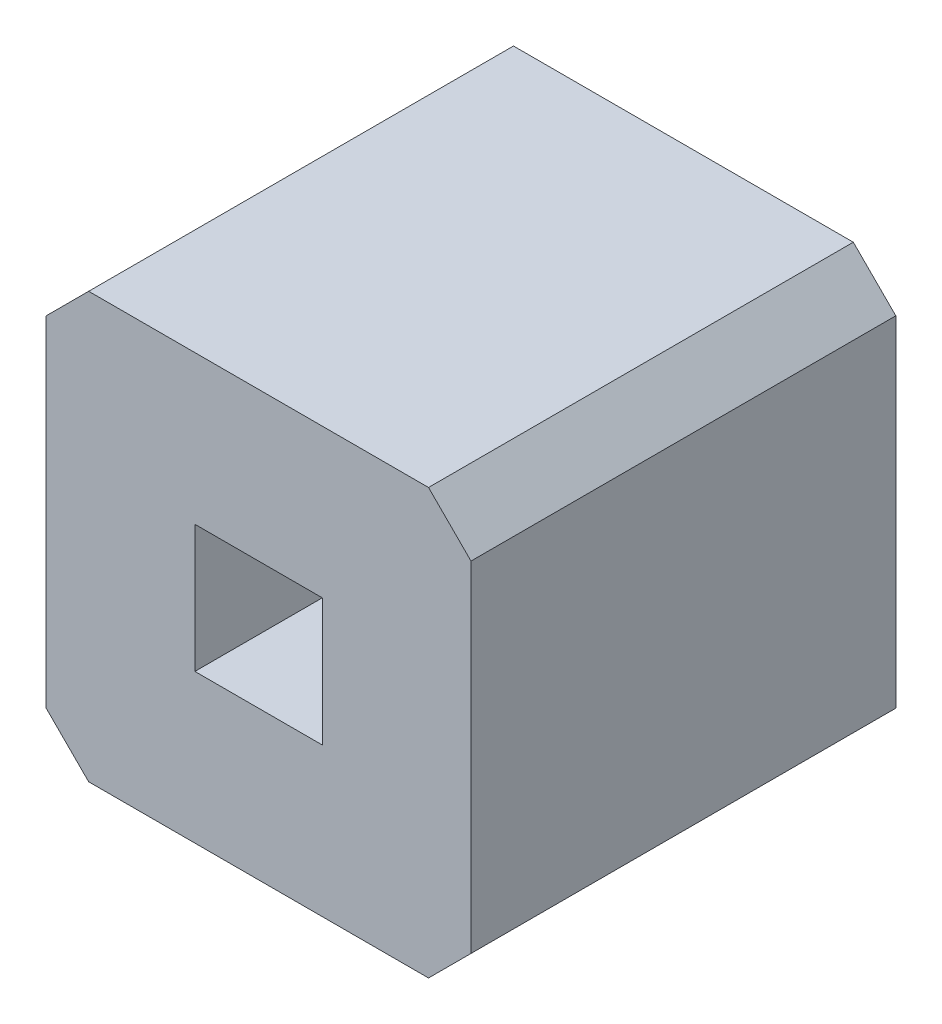
SolidWorks part; units mm, degrees
material "ABS"
ref_plane "Front Plane" through (0, 0, 0) normal (0, 0, 1) x (1, 0, 0)
ref_plane "Top Plane" through (0, 0, 0) normal (0, 1, 0) x (1, 0, 0)
ref_plane "Right Plane" through (0, 0, 0) normal (1, 0, 0) x (0, 0, -1)
sketch "Sketch1" plane through (0, 0, 0) normal (0, 0, 1) x (1, 0, 0)
  line L0 (0, 2.25) -> (0.25, 2.5)
  line L1 (0.25, 0) -> (2.25, 0)
  line L2 (0, 0.25) -> (0, 2.25)
  line L3 (0.25, 2.5) -> (2.25, 2.5)
  line L4 (2.5, 0.25) -> (2.5, 2.25)
  line L5 (0.875, 1.625) -> (1.625, 1.625)
  line L6 (0.875, 1.625) -> (0.875, 0.875)
  line L7 (0.875, 0.875) -> (1.625, 0.875)
  line L8 (1.625, 1.625) -> (1.625, 0.875)
  line L9 (2.25, 2.5) -> (2.5, 2.25)
  line L10 (0, 0.25) -> (0.25, 0)
  line L11 (2.25, 0) -> (2.5, 0.25)
  dimension "D1" = 2.5
  dimension "D2" = 2.5
  dimension "D3" = 0.75
  dimension "D4" = 0.75
  dimension "D5" = 0.875
  dimension "D6" = 0.875
  dimension "D7" = 0.25
  dimension "D8" = 0.25
  dimension "D9" = 0.25
  dimension "D10" = 0.25
  dimension "D11" = 0.25
  dimension "D12" = 0.25
  dimension "D13" = 0.25
  dimension "D14" = 0.25
  dimension "D15" = 0.25
extrude "Boss-Extrude1" add sketch "Sketch1" along normal blind 2.5
